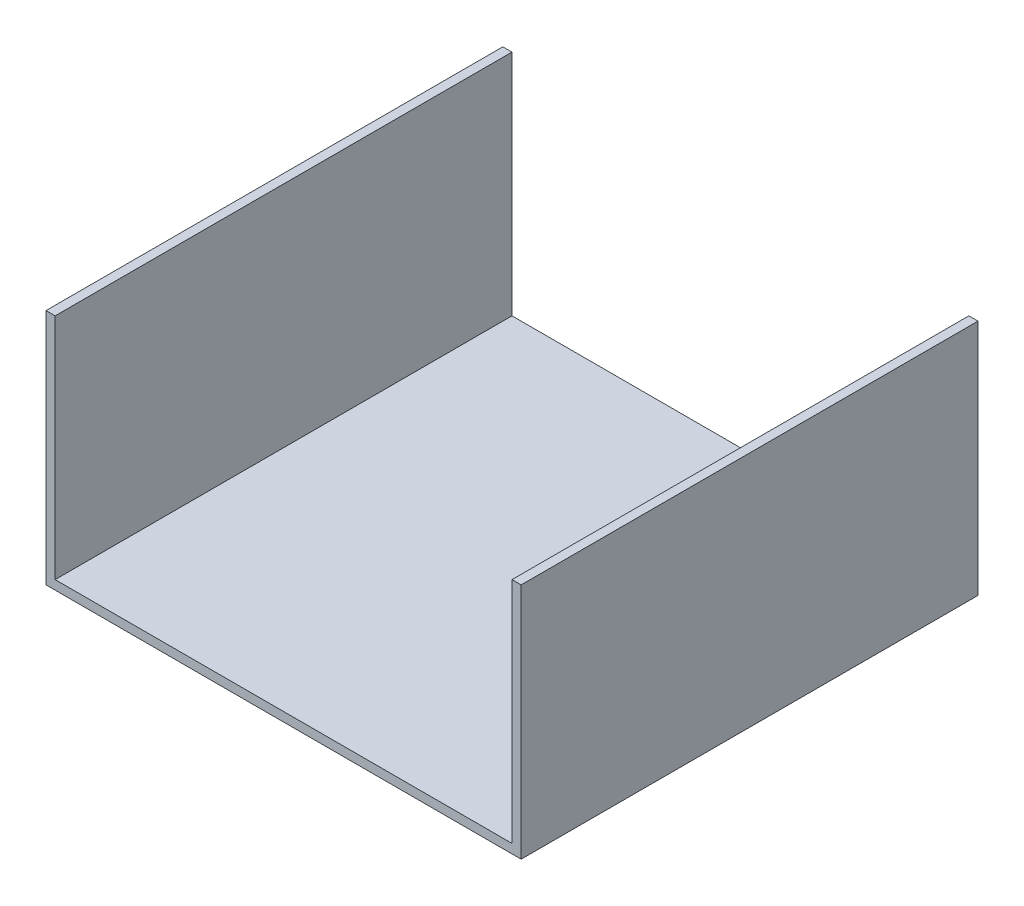
SolidWorks part; units mm, degrees
ref_plane "Front Plane" through (0, 0, 0) normal (0, 0, 1) x (1, 0, 0)
ref_plane "Top Plane" through (0, 0, 0) normal (0, 1, 0) x (1, 0, 0)
ref_plane "Right Plane" through (0, 0, 0) normal (1, 0, 0) x (0, 0, -1)
sketch "Sketch2" plane through (0, 0, 0) normal (0, 0, 1) x (1, 0, 0)
  line L0 (0, 0) -> (0, -5000)
  line L1 (0, -5000) -> (10000, -5000)
  line L2 (10000, -5000) -> (10000, 0)
  line L3 (-200, 0) -> (-200, -5200)
  line L4 (-200, -5200) -> (10200, -5200)
  line L5 (10200, -5200) -> (10200, 0)
  line L6 (-200, 0) -> (0, 0)
  line L7 (10000, 0) -> (10200, 0)
extrude "Boss-Extrude1" add sketch "Sketch2" against normal blind 10000
